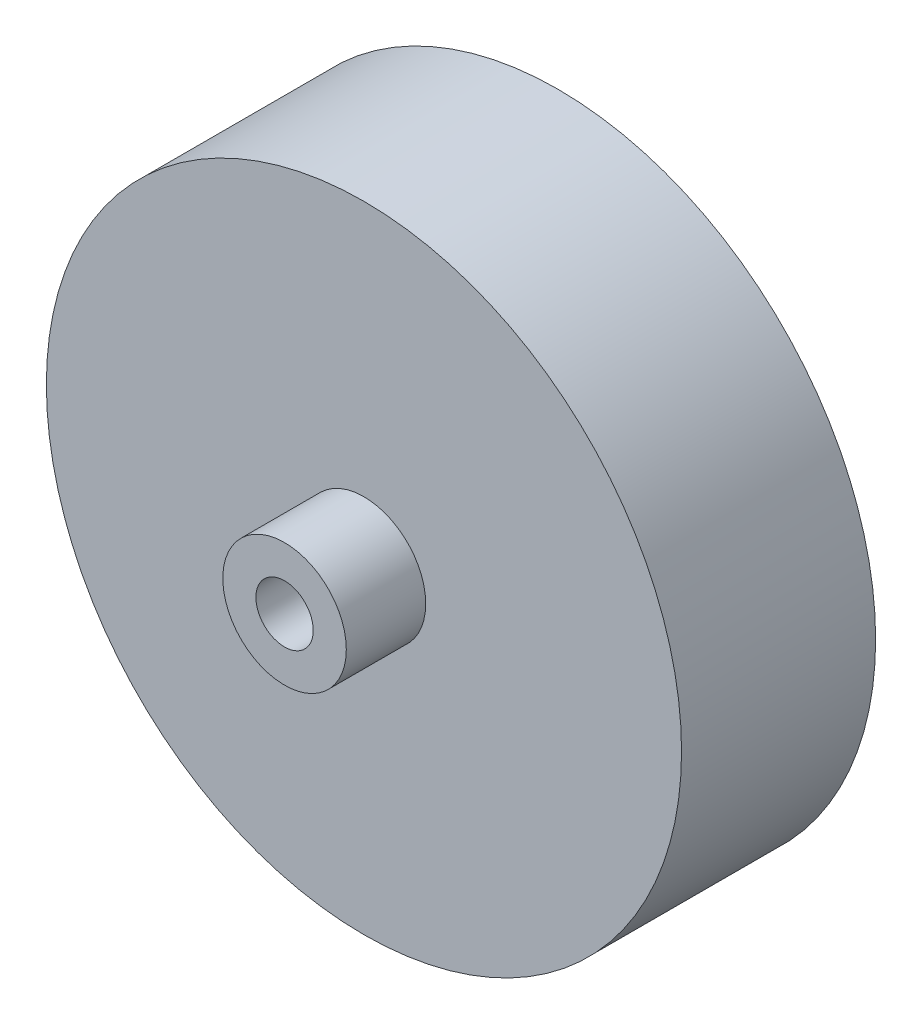
SolidWorks part; units mm, degrees
material "Rubber"
ref_plane "Front Plane" through (0, 0, 0) normal (0, 0, 1) x (1, 0, 0)
ref_plane "Top Plane" through (0, 0, 0) normal (0, 1, 0) x (1, 0, 0)
ref_plane "Right Plane" through (0, 0, 0) normal (1, 0, 0) x (0, 0, -1)
sketch "Sketch1" plane through (0, 0, 0) normal (0, 0, 1) x (1, 0, 0)
  circle A0 centre (0, 0) radius 36
  dimension "D1" = 72
extrude "Boss-Extrude1" add sketch "Sketch1" along normal blind 22
sketch "Sketch2" plane through (0, 0, 22) normal (0, 0, 1) x (1, 0, 0)
  circle A0 centre (0, 0) radius 7
  dimension "D1" = 14
extrude "Boss-Extrude2" add sketch "Sketch2" along normal blind 9
sketch "Sketch3" plane through (0, 0, 31) normal (0, 0, 1) x (1, 0, 0)
  circle A0 centre (0, 0) radius 3.25
  dimension "D1" = 6.5
extrude "Cut-Extrude1" cut sketch "Sketch3" against normal blind 31
sketch "Sketch4" plane through (0, 0, 31) normal (0, 0, 1) x (1, 0, 0)
  circle A0 centre (0, 0) radius 3.25
